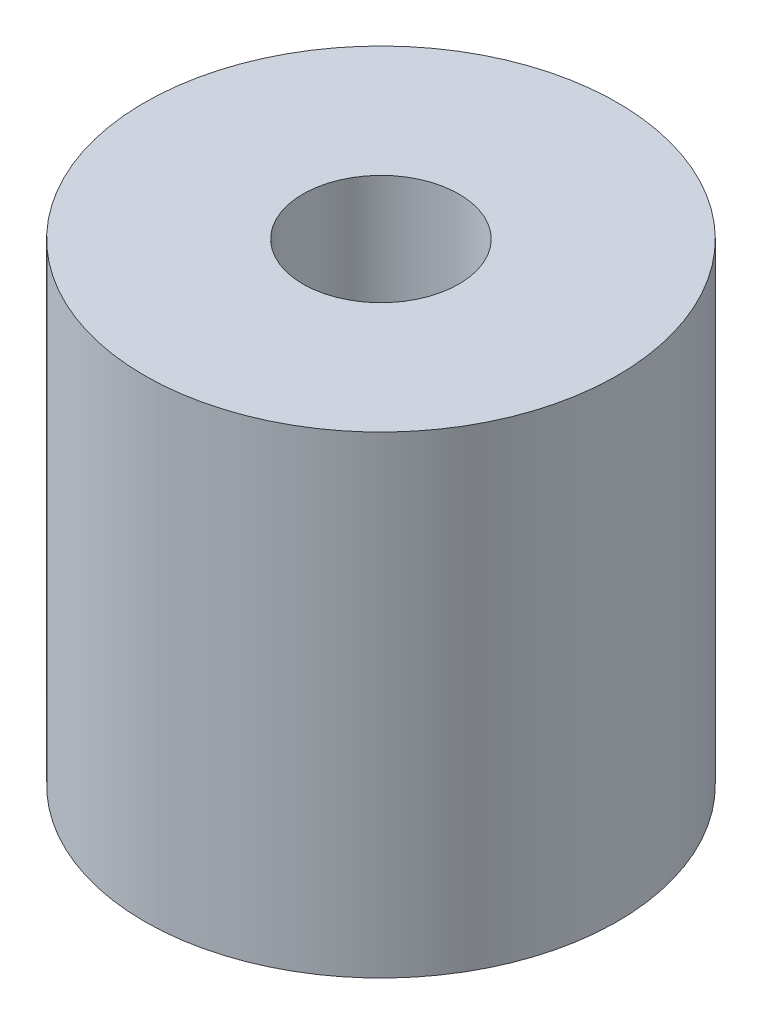
SolidWorks part; units mm, degrees
material "Nylon 101"
ref_plane "Front Plane" through (0, 0, 0) normal (0, 0, 1) x (1, 0, 0)
ref_plane "Top Plane" through (0, 0, 0) normal (0, 1, 0) x (1, 0, 0)
ref_plane "Right Plane" through (0, 0, 0) normal (1, 0, 0) x (0, 0, -1)
other "1/32"
sketch "Sketch1" plane through (0, 0, 0) normal (0, 1, 0) x (1, 0, 0)
  circle A0 centre (0, 0) radius 2.0955
  circle A1 centre (0, 0) radius 6.35
  dimension "D1" = 4.191
  dimension "D2" = 12.7
extrude "Boss-Extrude1" add sketch "Sketch1" along normal blind 12.7
